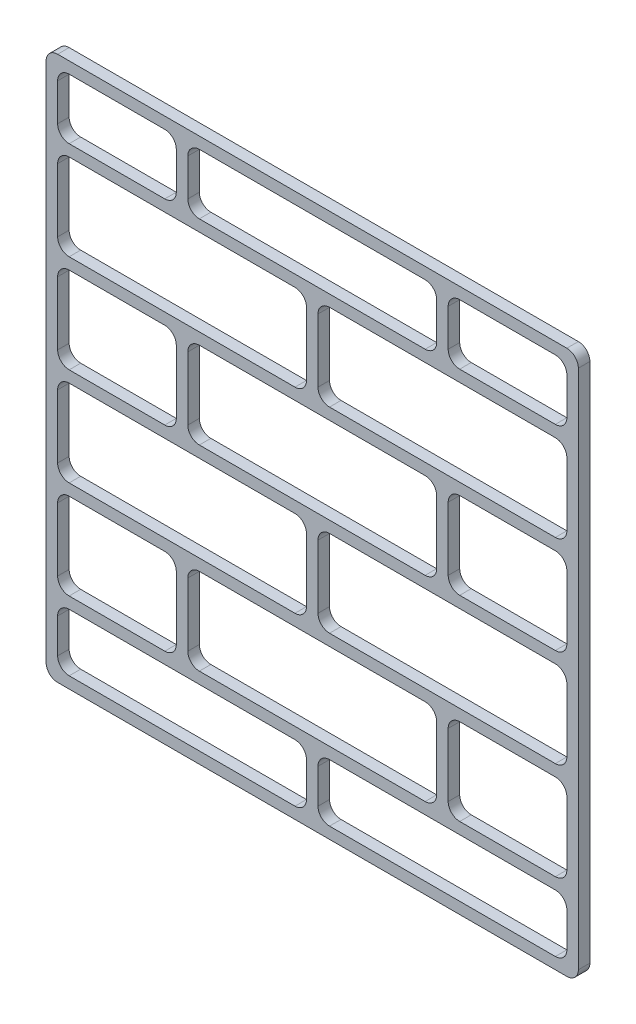
SolidWorks part; units mm, degrees
ref_plane "Ön Düzlem" through (0, 0, 0) normal (0, 0, 1) x (1, 0, 0)
ref_plane "Üst Düzlem" through (0, 0, 0) normal (0, 1, 0) x (1, 0, 0)
ref_plane "Sağ Düzlem" through (0, 0, 0) normal (1, 0, 0) x (0, 0, -1)
sketch "Çizim1" plane through (0, 0, 0) normal (0, 0, 1) x (1, 0, 0)
  line L0 (-44.2, 34.775) -> (-44.2, 45.225)
  line L1 (-46.2, -47.225) -> (46.2, -47.225)
  line L2 (-46.2, -47.225) -> (-46.2, 47.225)
  line L3 (-46.2, 47.225) -> (46.2, 47.225)
  line L4 (46.2, -47.225) -> (46.2, 47.225)
  line L5 (-46.2, -47.225) -> (46.2, 47.225) construction
  line L6 (-46.2, 47.225) -> (46.2, -47.225) construction
  line L7 (-44.2, -45.225) -> (-1, -45.225)
  line L8 (-44.2, -45.225) -> (-44.2, -35.225)
  line L9 (-44.2, 45.225) -> (-23.6, 45.225)
  line L10 (44.2, -45.225) -> (44.2, -35.225)
  line L11 (-44.2, -45.225) -> (44.2, 45.225) construction
  line L12 (-44.2, 45.225) -> (44.2, -45.225) construction
  line L13 (-44.2, -33.225) -> (-23.6, -33.225)
  line L15 (-44.2, -35.225) -> (-1, -35.225)
  line L17 (-44.2, -16.225) -> (-1, -16.225)
  line L19 (-44.2, -18.225) -> (-23.6, -18.225)
  line L21 (-44.2, 0.775) -> (-23.6, 0.775)
  line L23 (-44.2, -1.225) -> (-1, -1.225)
  line L25 (-44.2, 17.775) -> (-1, 17.775)
  line L27 (-44.2, 15.775) -> (-23.6, 15.775)
  line L29 (-44.2, 34.775) -> (-23.6, 34.775)
  line L31 (-44.2, 32.775) -> (-1, 32.775)
  line L33 (-44.2, 17.775) -> (-44.2, 32.775)
  line L34 (-44.2, 0.775) -> (-44.2, 15.775)
  line L35 (-44.2, -16.225) -> (-44.2, -1.225)
  line L36 (-44.2, -33.225) -> (-44.2, -18.225)
  line L37 (44.2, -33.225) -> (44.2, -18.225)
  line L38 (44.2, -16.225) -> (44.2, -1.225)
  line L39 (44.2, 0.775) -> (44.2, 15.775)
  line L40 (44.2, 17.775) -> (44.2, 32.775)
  line L41 (44.2, 34.775) -> (44.2, 45.225)
  line L42 (-44.2, 25.275) -> (-1, 25.275) construction
  line L44 (-23.6, 45.225) -> (-23.6, 34.775)
  line L46 (-21.6, 45.225) -> (-21.6, 34.775)
  line L48 (21.6, 45.225) -> (21.6, 34.775)
  line L50 (23.6, 45.225) -> (23.6, 34.775)
  line L52 (-1, 32.775) -> (-1, 17.775)
  line L54 (1, 32.775) -> (1, 17.775)
  line L56 (-23.6, 15.775) -> (-23.6, 0.775)
  line L58 (-21.6, 15.775) -> (-21.6, 0.775)
  line L60 (21.6, 15.775) -> (21.6, 0.775)
  line L62 (23.6, 15.775) -> (23.6, 0.775)
  line L64 (-1, -1.225) -> (-1, -16.225)
  line L66 (1, -1.225) -> (1, -16.225)
  line L68 (-21.6, -18.225) -> (-21.6, -33.225)
  line L70 (-23.6, -18.225) -> (-23.6, -33.225)
  line L72 (21.6, -18.225) -> (21.6, -33.225)
  line L74 (23.6, -18.225) -> (23.6, -33.225)
  line L76 (-1, -35.225) -> (-1, -45.225)
  line L78 (1, -35.225) -> (1, -45.225)
  line L79 (-23.6, 40) -> (-21.6, 40) construction
  line L80 (21.6, 40) -> (23.6, 40) construction
  line L81 (-23.6, 8.275) -> (-21.6, 8.275) construction
  line L82 (21.6, 8.275) -> (23.6, 8.275) construction
  line L83 (-23.6, -25.725) -> (-21.6, -25.725) construction
  line L84 (21.6, -25.725) -> (23.6, -25.725) construction
  line L85 (1, 25.275) -> (44.2, 25.275) construction
  line L86 (-21.6, -18.225) -> (21.6, -18.225)
  line L87 (-21.6, -33.225) -> (21.6, -33.225)
  line L88 (1, -35.225) -> (44.2, -35.225)
  line L89 (1, -45.225) -> (44.2, -45.225)
  line L90 (23.6, -33.225) -> (44.2, -33.225)
  line L91 (23.6, -18.225) -> (44.2, -18.225)
  line L92 (1, -16.225) -> (44.2, -16.225)
  line L93 (1, -1.225) -> (44.2, -1.225)
  line L94 (-21.6, 0.775) -> (21.6, 0.775)
  line L95 (23.6, 0.775) -> (44.2, 0.775)
  line L96 (-21.6, 15.775) -> (21.6, 15.775)
  line L97 (23.6, 15.775) -> (44.2, 15.775)
  line L98 (1, 17.775) -> (44.2, 17.775)
  line L99 (1, 32.775) -> (44.2, 32.775)
  line L100 (-1, 25.275) -> (1, 25.275) construction
  line L101 (-1, -8.725) -> (1, -8.725) construction
  line L102 (-1, -40.225) -> (1, -40.225) construction
  line L103 (-21.6, 45.225) -> (21.6, 45.225)
  line L104 (-21.6, 34.775) -> (21.6, 34.775)
  line L105 (23.6, 34.775) -> (44.2, 34.775)
  line L106 (23.6, 45.225) -> (44.2, 45.225)
  point P0 (0, 0)
  point P6 (0, 0)
  point P70 (0, 25.275)
  point P77 (0, -40.225)
  point P87 (-22.6, 40)
  point P88 (-22.6, 25.275)
  point P91 (22.6, 40)
  point P92 (22.6, 25.275)
  point P93 (22.6, 8.275)
  point P94 (-22.6, 8.275)
  point P95 (-22.6, -25.725)
  point P96 (22.6, -25.725)
  point P97 (0, -8.725)
  dimension "D1" = 2
  dimension "D2" = 2
  dimension "D3" = 92.4
  dimension "D4" = 94.45
  dimension "D5" = 2
  dimension "D6" = 10
  dimension "D7" = 15
  dimension "D8" = 2
  dimension "D9" = 15
  dimension "D10" = 2
  dimension "D11" = 15
  dimension "D12" = 2
  dimension "D13" = 15
  dimension "D14" = 2
  dimension "D15" = 2
  dimension "D16" = 2
  dimension "D17" = 2
  dimension "D18" = 2
  dimension "D19" = 2
  dimension "D20" = 2
  dimension "D21" = 2
  dimension "D22" = 2
  dimension "D23" = 2
extrude "Yükseklik-Ekstrüzyon1" add sketch "Çizim1" along normal blind 2
fillet "Radyus1" radius 2 64 edges at (46.2, -47.225, 1) (-46.2, -47.225, 1) (-46.2, 47.225, 1) (46.2, 47.225, 1) (-21.6, -18.225, 1) (-21.6, -33.225, 1) (21.6, -33.225, 1) (21.6, -18.225, 1) (21.6, 34.775, 1) (21.6, 45.225, 1) (-21.6, 45.225, 1) (-21.6, 34.775, 1) (-44.2, 17.775, 1) (-1, 17.775, 1) (-1, 32.775, 1) (-44.2, 32.775, 1) (-44.2, 0.775, 1) (-23.6, 0.775, 1) (-23.6, 15.775, 1) (-44.2, 15.775, 1) (-44.2, -16.225, 1) (-1, -16.225, 1) (-1, -1.225, 1) (-44.2, -1.225, 1) (-44.2, -33.225, 1) (-23.6, -33.225, 1) (-23.6, -18.225, 1) (-44.2, -18.225, 1) (-44.2, 34.775, 1) (-23.6, 34.775, 1) (-23.6, 45.225, 1) (23.6, 45.225, 1) (23.6, 34.775, 1) (44.2, 34.775, 1) (44.2, 45.225, 1) (-44.2, -45.225, 1) (-1, -45.225, 1) (-1, -35.225, 1) (-44.2, -35.225, 1) (44.2, -45.225, 1) (44.2, -35.225, 1) (1, -35.225, 1) (1, -45.225, 1) (44.2, -33.225, 1) (44.2, -18.225, 1) (23.6, -18.225, 1) (23.6, -33.225, 1) (44.2, -16.225, 1) (44.2, -1.225, 1) (1, -1.225, 1) (1, -16.225, 1) (44.2, 0.775, 1) (44.2, 15.775, 1) (23.6, 15.775, 1) (23.6, 0.775, 1) (44.2, 17.775, 1) (44.2, 32.775, 1) (1, 32.775, 1) (1, 17.775, 1) (21.6, 0.775, 1) (21.6, 15.775, 1) (-21.6, 15.775, 1) (-21.6, 0.775, 1) (-44.2, 45.225, 1)
